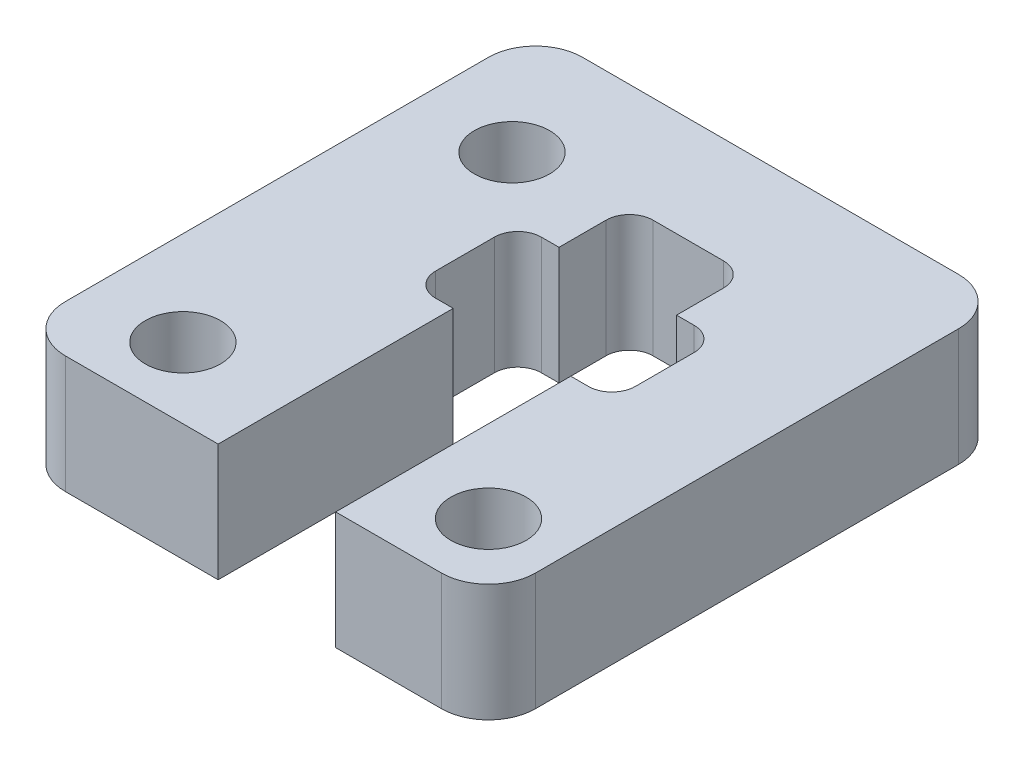
SolidWorks part; units mm, degrees
material "碳纤维"
ref_plane "前视基准面" through (0, 0, 0) normal (0, 0, 1) x (1, 0, 0)
ref_plane "上视基准面" through (0, 0, 0) normal (0, 1, 0) x (1, 0, 0)
ref_plane "右视基准面" through (0, 0, 0) normal (1, 0, 0) x (0, 0, -1)
sketch "草图2" plane through (0, 0, 0) normal (0, 1, 0) x (1, 0, 0)
  line L1 (-10, -10) -> (10, -10)
  line L2 (-10, -10) -> (-10, 10)
  line L3 (-10, 10) -> (10, 10) construction
  line L5 (0, 10) -> (0, -10) construction
  line L6 (-10, 0) -> (10, 0) construction
  line L11 (10, 10) -> (10, -10)
  line L12 (1, 0) -> (1, -10) construction
  line L20 (-3.25, 0) -> (5.25, 0)
  line L21 (-3.25, 0) -> (-3.25, 4.5)
  line L22 (-3.25, 4.5) -> (5.25, 4.5)
  line L23 (5.25, 0) -> (5.25, 4.5)
  line L25 (-10, 10) -> (10, 10) construction
  line L26 (-10, 10) -> (-10, 12)
  line L27 (-10, 12) -> (10, 12)
  line L28 (10, 10) -> (10, 12)
  line L29 (0, 12) -> (0, 10) construction
  line L30 (-10, 11) -> (10, 11) construction
  circle A0 centre (-6, 7) radius 1.6
  circle A1 centre (-6, -7) radius 1.6
  circle A2 centre (7, -7) radius 1.6
  point P147 (0, 11)
  dimension "D2" = 3.2
  dimension "D1" = 14
  dimension "D3" = 20
  dimension "D4" = 4
  dimension "D5" = 20
  dimension "D6" = 4.5
  dimension "D7" = 8.5
  dimension "D8" = 7
  dimension "D9" = 3
  dimension "D10" = 2
extrude "凸台-拉伸1" add sketch "草图2" along normal blind 5
sketch "草图3" plane through (0, 0, 0) normal (0, -1, 0) x (1, 0, 0)
  line L5 (-10, 10) -> (10, 10) construction
  line L6 (-1.5, 10) -> (3.5, 10)
  line L8 (-1.5, 10) -> (-1.5, -7.5)
  line L9 (-1.5, -7.5) -> (3.5, -7.5)
  line L10 (3.5, 10) -> (3.5, -7.5)
  line L11 (1, -7.5) -> (1, 10) construction
  line L12 (-1.5, 1.25) -> (3.5, 1.25) construction
  line L13 (1, -4.5) -> (1, -7.5) construction
  line L14 (-3.25, -4.5) -> (5.25, -4.5) construction
  point P0 (1, 1.25)
  dimension "D1" = 5
  dimension "D2" = 3
extrude "切除-拉伸1" cut sketch "草图3" against normal through all
fillet "圆角1" radius 2 4 edges at (-10, 2.5, 10) (10, 2.5, 10) (10, 2.5, -12) (-10, 2.5, -12)
fillet "圆角2" radius 1 6 edges at (-1.5, 2.5, -7.5) (3.5, 2.5, -7.5) (5.25, 2.5, -4.5) (5.25, 2.5, 0) (-3.25, 2.5, -4.5) (-3.25, 2.5, 0)
